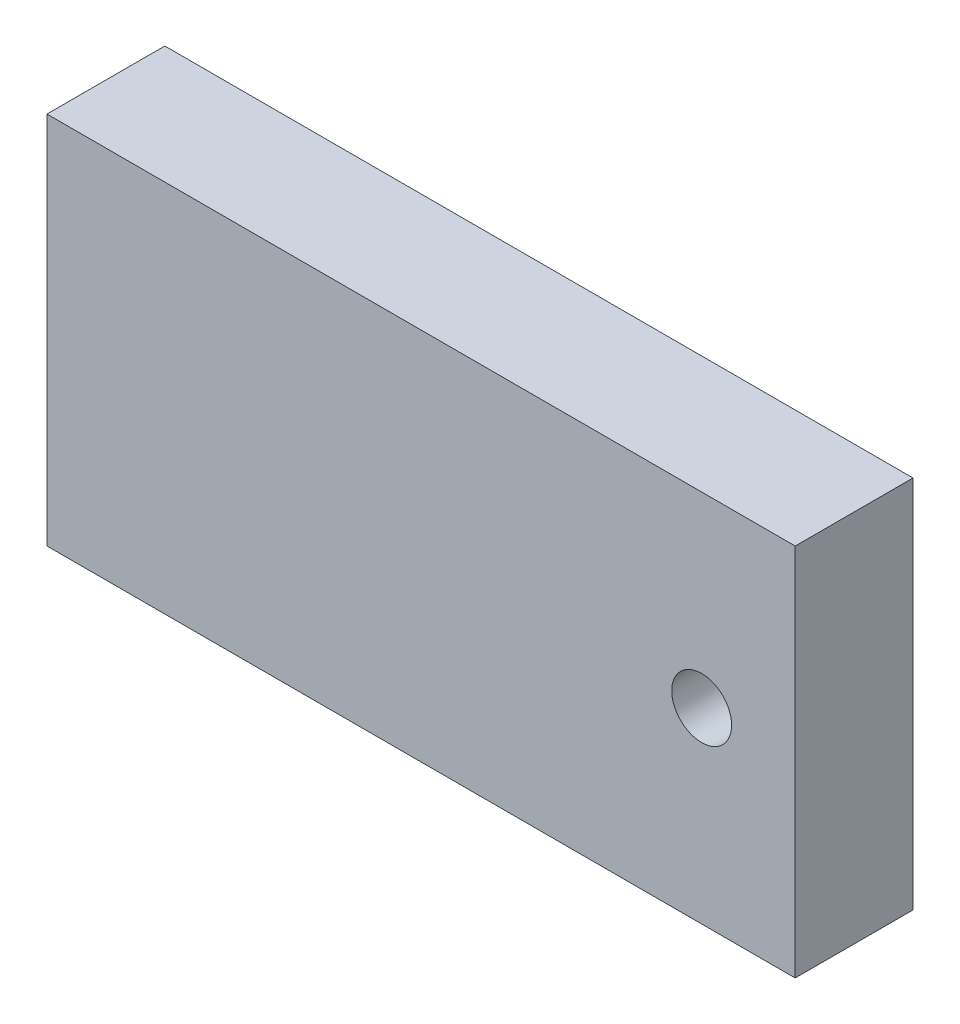
SolidWorks part; units mm, degrees
ref_plane "Front Plane" through (0, 0, 0) normal (0, 0, 1) x (1, 0, 0)
ref_plane "Top Plane" through (0, 0, 0) normal (0, 1, 0) x (1, 0, 0)
ref_plane "Right Plane" through (0, 0, 0) normal (1, 0, 0) x (0, 0, -1)
sketch "Sketch1" plane through (0, 0, 0) normal (0, 0, 1) x (1, 0, 0)
  line L0 (38.1, 9.525) -> (33.3375, 9.525) construction
  line L1 (0, 0) -> (38.1, 0)
  line L2 (0, 0) -> (0, 19.05)
  line L3 (0, 19.05) -> (38.1, 19.05)
  line L4 (38.1, 0) -> (38.1, 19.05)
  circle A0 centre (33.3375, 9.525) radius 1.524
  dimension "D4" = 3.048
  dimension "D1" = 19.05
  dimension "D2" = 38.1
  dimension "D3" = 4.7625
extrude "Boss-Extrude1" add sketch "Sketch1" along normal blind 6
